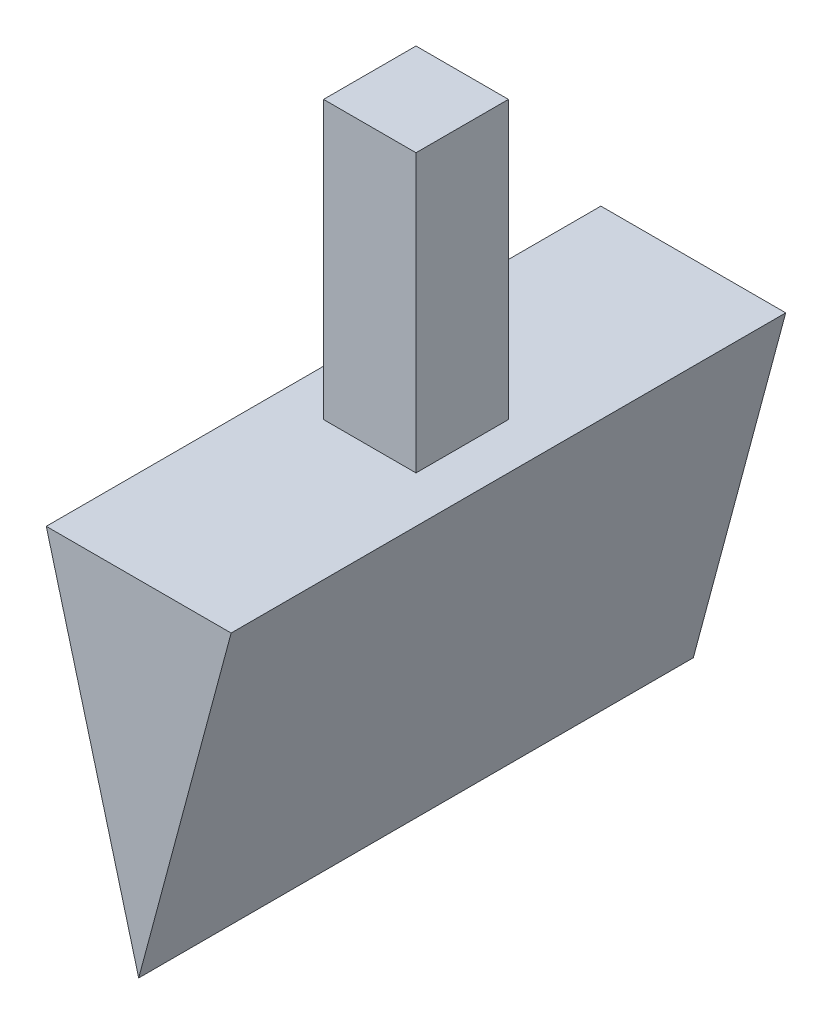
SolidWorks part; units mm, degrees
ref_plane "Plan de face" through (0, 0, 0) normal (0, 0, 1) x (1, 0, 0)
ref_plane "Plan de dessus" through (0, 0, 0) normal (0, 1, 0) x (1, 0, 0)
ref_plane "Plan de droite" through (0, 0, 0) normal (1, 0, 0) x (0, 0, -1)
sketch "Esquisse1" plane through (0, 0, 0) normal (0, 0, 1) x (1, 0, 0)
  line L0 (0, 0) -> (-2, 7.4641)
  line L1 (-2, 7.4641) -> (2, 7.4641)
  line L2 (0, 0) -> (2, 7.4641)
  dimension "D1" = 30
  dimension "D2" = 75
  dimension "D3" = 4
extrude "Boss.-Extru.1" add sketch "Esquisse1" along normal blind 12
sketch "Esquisse2" plane through (0, 7.4641, 0) normal (0, 1, 0) x (-1, 0, 0)
  line L1 (-1, 7) -> (1, 7)
  line L2 (-1, 7) -> (-1, 5)
  line L3 (-1, 5) -> (1, 5)
  line L4 (1, 7) -> (1, 5)
  line L5 (-2, 0) -> (2, 0) construction
  line L6 (-2, 12) -> (-2, 0) construction
  point P4 (-2, 6)
  dimension "D1" = 2
  dimension "D2" = 2
  dimension "D3" = 5
  dimension "D4" = 1
extrude "Boss.-Extru.2" add sketch "Esquisse2" along normal blind 6
